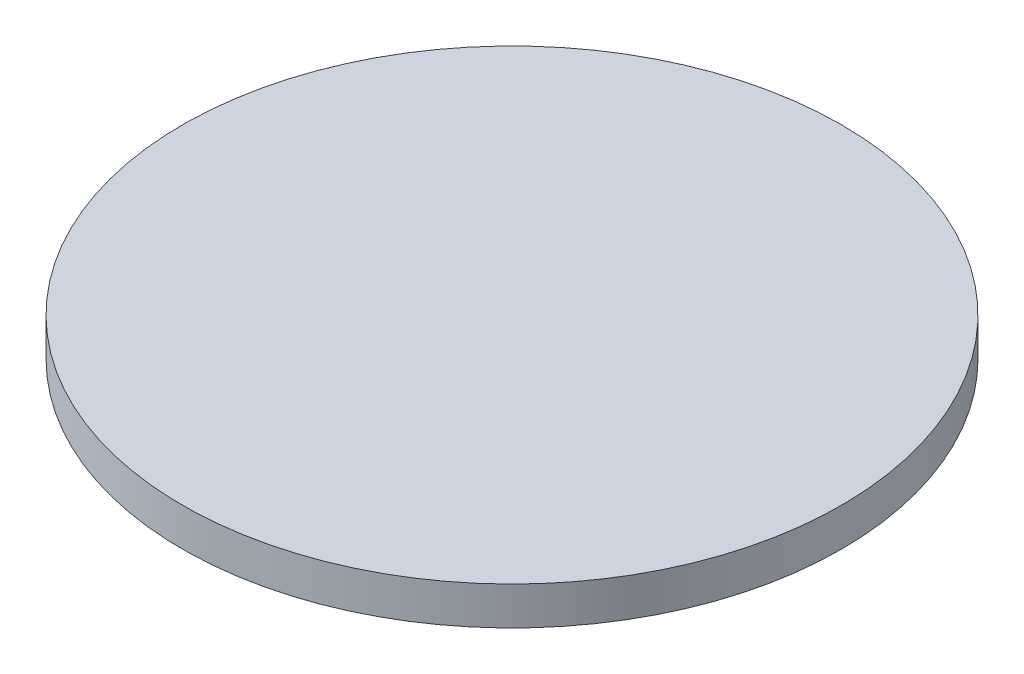
SolidWorks part; units mm, degrees
material "PC High Viscosity"
ref_plane "Front Plane" through (0, 0, 0) normal (0, 0, 1) x (1, 0, 0)
ref_plane "Top Plane" through (0, 0, 0) normal (0, 1, 0) x (1, 0, 0)
ref_plane "Right Plane" through (0, 0, 0) normal (1, 0, 0) x (0, 0, -1)
sketch "Sketch1" plane through (0, 0, 0) normal (0, 0, 1) x (1, 0, 0)
  line L0 (0, 0) -> (0, 29)
  line L1 (0, 29) -> (95.25, 29) construction
  line L2 (0, 0) -> (-11.5882, 0) construction
  line L4 (0, 29) -> (95.25, 29) construction
  line L5 (0, 29) -> (0, 40)
  line L6 (0, 40) -> (95.25, 40)
  line L7 (95.25, 29) -> (95.25, 40)
  arc A0 (0, 0) -> (95.25, 29) centre (0, 170.9235) ccw
  dimension "D1" = 95.25
  dimension "D2" = 11
  dimension "D3" = 29
revolve "Revolve1" add sketch "Sketch1" angle 360 about L0
ref_plane "Plane1" through (0, 0, 0) normal (0, -1, 0) x (-1, 0, 0)
